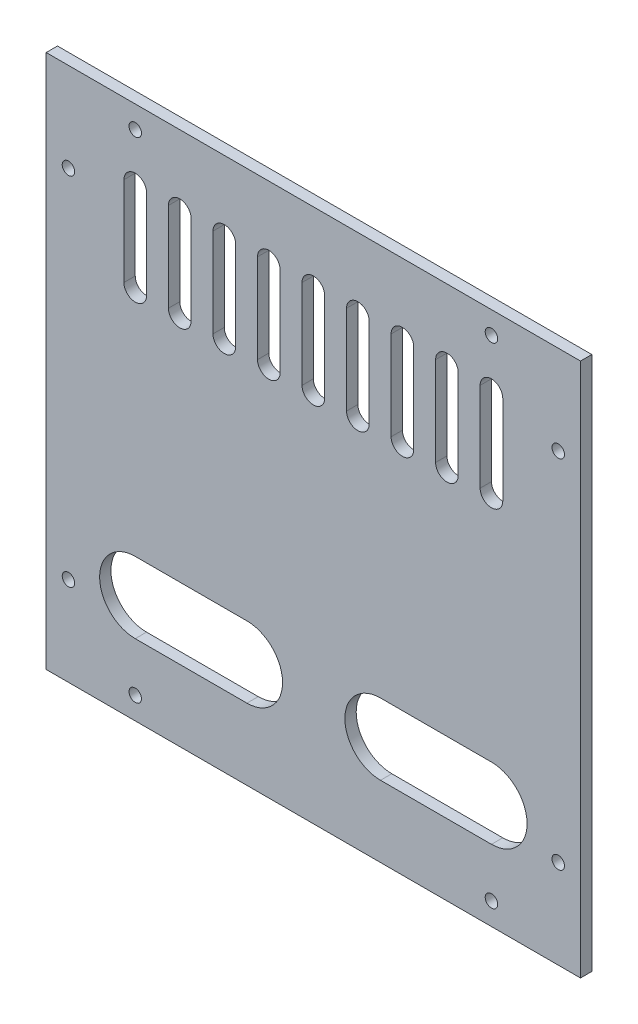
SolidWorks part; units mm, degrees
material "Acrylic (Medium-high impact)"
ref_plane "Front Plane" through (0, 0, 0) normal (0, 0, 1) x (1, 0, 0)
ref_plane "Top Plane" through (0, 0, 0) normal (0, 1, 0) x (1, 0, 0)
ref_plane "Right Plane" through (0, 0, 0) normal (1, 0, 0) x (0, 0, -1)
sketch "Sketch1" plane through (0, 0, 0) normal (0, 0, 1) x (1, 0, 0)
  line L1 (0, 0) -> (300, 0)
  line L2 (0, 0) -> (0, 300)
  line L3 (0, 300) -> (300, 300)
  line L4 (300, 0) -> (300, 300)
  dimension "D1" = 300
  dimension "D2" = 300
extrude "Boss-Extrude1" add sketch "Sketch1" along normal blind 6.35
sketch "Sketch2" plane through (0, 0, 6.35) normal (0, 0, 1) x (1, 0, 0)
  line L0 (150, 300) -> (150, 235) construction
  line L1 (300, 300) -> (0, 300) construction
  line L2 (150, 210) -> (150, 260) construction
  line L3 (143.65, 210) -> (143.65, 260)
  line L4 (156.35, 210) -> (156.35, 260)
  line L5 (181.35, 210) -> (181.35, 260)
  line L6 (168.65, 210) -> (168.65, 260)
  line L7 (175, 210) -> (175, 260) construction
  line L8 (206.35, 210) -> (206.35, 260)
  line L9 (193.65, 210) -> (193.65, 260)
  line L10 (200, 210) -> (200, 260) construction
  line L11 (231.35, 210) -> (231.35, 260)
  line L12 (218.65, 210) -> (218.65, 260)
  line L13 (225, 210) -> (225, 260) construction
  line L14 (256.35, 210) -> (256.35, 260)
  line L15 (243.65, 210) -> (243.65, 260)
  line L16 (250, 210) -> (250, 260) construction
  line L17 (131.35, 210) -> (131.35, 260)
  line L18 (118.65, 210) -> (118.65, 260)
  line L19 (125, 210) -> (125, 260) construction
  line L20 (106.35, 210) -> (106.35, 260)
  line L21 (93.65, 210) -> (93.65, 260)
  line L22 (100, 210) -> (100, 260) construction
  line L23 (81.35, 210) -> (81.35, 260)
  line L24 (68.65, 210) -> (68.65, 260)
  line L25 (75, 210) -> (75, 260) construction
  line L26 (56.35, 210) -> (56.35, 260)
  line L27 (43.65, 210) -> (43.65, 260)
  line L28 (50, 210) -> (50, 260) construction
  arc A0 (143.65, 210) -> (156.35, 210) centre (150, 210) ccw
  arc A1 (156.35, 260) -> (143.65, 260) centre (150, 260) ccw
  arc A2 (168.65, 210) -> (181.35, 210) centre (175, 210) ccw
  arc A3 (181.35, 260) -> (168.65, 260) centre (175, 260) ccw
  arc A4 (193.65, 210) -> (206.35, 210) centre (200, 210) ccw
  arc A5 (206.35, 260) -> (193.65, 260) centre (200, 260) ccw
  arc A6 (218.65, 210) -> (231.35, 210) centre (225, 210) ccw
  arc A7 (231.35, 260) -> (218.65, 260) centre (225, 260) ccw
  arc A8 (243.65, 210) -> (256.35, 210) centre (250, 210) ccw
  arc A9 (256.35, 260) -> (243.65, 260) centre (250, 260) ccw
  arc A10 (118.65, 210) -> (131.35, 210) centre (125, 210) ccw
  arc A11 (131.35, 260) -> (118.65, 260) centre (125, 260) ccw
  arc A12 (93.65, 210) -> (106.35, 210) centre (100, 210) ccw
  arc A13 (106.35, 260) -> (93.65, 260) centre (100, 260) ccw
  arc A14 (68.65, 210) -> (81.35, 210) centre (75, 210) ccw
  arc A15 (81.35, 260) -> (68.65, 260) centre (75, 260) ccw
  arc A16 (43.65, 210) -> (56.35, 210) centre (50, 210) ccw
  arc A17 (56.35, 260) -> (43.65, 260) centre (50, 260) ccw
  point P6 (150, 235)
  point P14 (175, 235)
  point P21 (200, 235)
  point P28 (225, 235)
  point P35 (250, 235)
  point P43 (125, 235)
  point P50 (100, 235)
  point P57 (75, 235)
  point P64 (50, 235)
  dimension "D3" = 6.35
  dimension "D1" = 65
  dimension "D2" = 25
  dimension "D6" = 25
  dimension "D7" = 25
  dimension "D4" = 5
  dimension "D5" = 5
extrude "Cut-Extrude1" cut sketch "Sketch2" against normal up to surface (6.35 mm away) up to face at (150, 150, 0)
sketch "Sketch3" plane through (0, 0, 6.35) normal (0, 0, 1) x (1, 0, 0)
  line L0 (150, 0) -> (150, 60) construction
  line L1 (0, 0) -> (300, 0) construction
  line L2 (250, 60) -> (50, 60) construction
  line L3 (50, 60) -> (112.7088, 60) construction
  line L4 (50, 80) -> (112.7088, 80)
  line L5 (50, 40) -> (112.7088, 40)
  line L6 (250, 60) -> (187.7088, 60) construction
  line L7 (250, 40) -> (187.7088, 40)
  line L8 (250, 80) -> (187.7088, 80)
  arc A0 (50, 80) -> (50, 40) centre (50, 60) ccw
  arc A1 (112.7088, 40) -> (112.7088, 80) centre (112.7088, 60) ccw
  arc A2 (250, 40) -> (250, 80) centre (250, 60) ccw
  arc A3 (187.7088, 80) -> (187.7088, 40) centre (187.7088, 60) ccw
  point P7 (150, 60)
  point P8 (81.3544, 60)
  point P13 (218.8544, 60)
  dimension "D3" = 20
  dimension "D1" = 60
  dimension "D2" = 200
  dimension "D4" = 75
extrude "Cut-Extrude2" cut sketch "Sketch3" against normal through all
ref_plane "Plane1" through (150, 0, 0) normal (-1, 0, 0) x (0, 0, 1)
ref_plane "Plane2" through (0, 150, 0) normal (0, 1, 0) x (1, 0, 0)
sketch "Sketch4" plane through (0, 0, 6.35) normal (0, 0, 1) x (1, 0, 0)
  line L0 (50, 300) -> (50, 287.5) construction
  line L1 (50, 287.5) -> (250, 287.5) construction
  line L2 (0, 300) -> (0, 0) construction
  line L3 (300, 300) -> (0, 300) construction
  line L4 (0, 150) -> (12.5, 150) construction
  line L5 (12.5, 150) -> (12.5, 50) construction
  line L6 (150, 3.4925) -> (150, -3.4925) construction
  line L7 (12.5, 150) -> (12.5, 250) construction
  line L8 (3.4925, 150) -> (-3.4925, 150) construction
  circle A1 centre (50, 287.5) radius 3.5
  circle A2 centre (250, 287.5) radius 3.5
  circle A3 centre (12.5, 150) radius 3.5 construction
  circle A4 centre (12.5, 50) radius 3.5
  circle A5 centre (12.5, 250) radius 3.5
  circle A6 centre (287.5, 50) radius 3.5
  circle A7 centre (287.5, 150) radius 3.5 construction
  circle A8 centre (287.5, 250) radius 3.5
  circle A9 centre (250, 12.5) radius 3.5
  circle A10 centre (50, 12.5) radius 3.5
  point P5 (50, 293.75)
  dimension "D2" = 7
  dimension "D4" = 2
  dimension "D7" = 7
  dimension "D1" = 12.5
  dimension "D3" = 50
  dimension "D5" = 200
  dimension "D6" = 12.5
  dimension "D9" = 100
  dimension "D11" = 100
  dimension "D8" = 2
  dimension "D10" = 2
extrude "Cut-Extrude3" cut sketch "Sketch4" against normal blind 10
